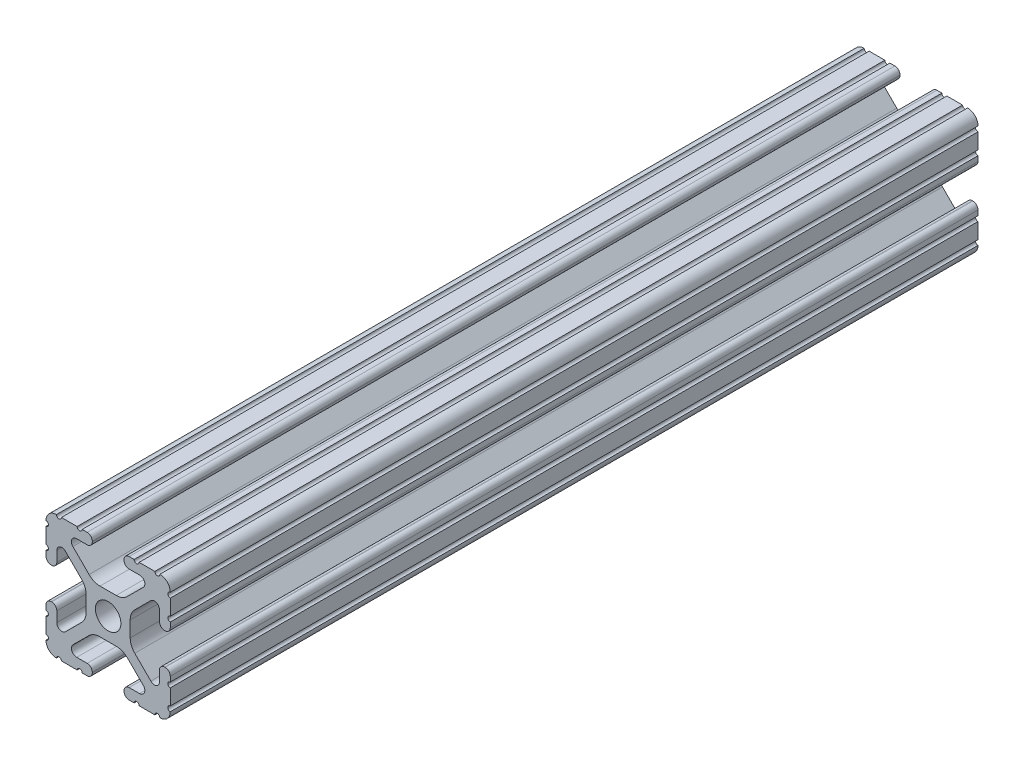
SolidWorks part; units mm, degrees
ref_plane "Front Plane" through (0, 0, 0) normal (0, 0, 1) x (1, 0, 0)
ref_plane "Top Plane" through (0, 0, 0) normal (0, 1, 0) x (1, 0, 0)
ref_plane "Right Plane" through (0, 0, 0) normal (1, 0, 0) x (0, 0, -1)
sketch "Sketch1" plane through (0, 0, 0) normal (0, 0, 1) x (1, 0, 0)
  line L88 (-7.1797, -8.6452) -> (-3.9523, -5.4237)
  line L89 (-1.7093, -4.4958) -> (1.7093, -4.4958)
  line L90 (3.9523, -5.4237) -> (7.1797, -8.6452)
  line L91 (6.4164, -10.4902) -> (4.2875, -10.4902)
  line L92 (3.2385, -11.5392) -> (3.2385, -11.651)
  line L93 (4.2875, -12.7) -> (5.3171, -12.7)
  line L94 (6.3331, -12.7) -> (9.5504, -12.7)
  line L95 (12.7, -9.5504) -> (12.7, -6.3331)
  line L96 (12.7, -5.3171) -> (12.7, -4.2875)
  line L97 (11.651, -3.2385) -> (11.5392, -3.2385)
  line L98 (10.4902, -4.2875) -> (10.4902, -6.4021)
  line L99 (8.7371, -7.1294) -> (5.441, -3.8408)
  line L100 (4.5085, -1.5932) -> (4.5085, 1.5932)
  line L101 (5.441, 3.8408) -> (8.7371, 7.1294)
  line L102 (10.4902, 6.4021) -> (10.4902, 4.2875)
  line L103 (11.5392, 3.2385) -> (11.651, 3.2385)
  line L104 (12.7, 4.2875) -> (12.7, 5.3171)
  line L105 (12.7, 6.3331) -> (12.7, 9.5504)
  line L106 (9.5504, 12.7) -> (6.3331, 12.7)
  line L107 (5.3171, 12.7) -> (4.2875, 12.7)
  line L108 (3.2385, 11.651) -> (3.2385, 11.5392)
  line L109 (4.2875, 10.4902) -> (6.4768, 10.4902)
  line L110 (7.207, 8.7244) -> (3.8983, 5.4232)
  line L111 (1.6558, 4.4958) -> (-1.6558, 4.4958)
  line L112 (-3.8983, 5.4232) -> (-7.207, 8.7244)
  line L113 (-6.4768, 10.4902) -> (-4.2875, 10.4902)
  line L114 (-3.2385, 11.5392) -> (-3.2385, 11.651)
  line L115 (-4.2875, 12.7) -> (-5.3171, 12.7)
  line L116 (-6.3331, 12.7) -> (-9.5504, 12.7)
  line L117 (-12.7, 9.5504) -> (-12.7, 6.3331)
  line L118 (-12.7, 5.3171) -> (-12.7, 4.2875)
  line L119 (-11.651, 3.2385) -> (-11.5392, 3.2385)
  line L120 (-10.4902, 4.2875) -> (-10.4902, 6.4021)
  line L121 (-8.7371, 7.1294) -> (-5.441, 3.8408)
  line L122 (-4.5085, 1.5932) -> (-4.5085, -1.5932)
  line L123 (-5.441, -3.8408) -> (-8.7371, -7.1294)
  line L124 (-10.4902, -6.4021) -> (-10.4902, -4.2875)
  line L125 (-11.5392, -3.2385) -> (-11.651, -3.2385)
  line L126 (-12.7, -4.2875) -> (-12.7, -5.3171)
  line L127 (-12.7, -6.3331) -> (-12.7, -9.5504)
  line L128 (-9.5504, -12.7) -> (-6.3331, -12.7)
  line L129 (-5.3171, -12.7) -> (-4.2875, -12.7)
  line L130 (-3.2385, -11.651) -> (-3.2385, -11.5392)
  line L131 (-4.2875, -10.4902) -> (-6.4164, -10.4902)
  circle A1 centre (0, 0) radius 2.6035
  arc A104 (-7.1797, -8.6452) -> (-6.4164, -10.4902) centre (-6.4164, -9.4098) ccw
  arc A105 (-1.7093, -4.4958) -> (-3.9523, -5.4237) centre (-1.7093, -7.6708) ccw
  arc A106 (3.9523, -5.4237) -> (1.7093, -4.4958) centre (1.7093, -7.6708) ccw
  arc A107 (6.4164, -10.4902) -> (7.1797, -8.6452) centre (6.4164, -9.4098) ccw
  arc A108 (4.2875, -10.4902) -> (3.2385, -11.5392) centre (4.2875, -11.5392) ccw
  arc A109 (3.2385, -11.651) -> (4.2875, -12.7) centre (4.2875, -11.651) ccw
  arc A110 (6.3331, -12.7) -> (5.3171, -12.7) centre (5.8251, -12.7) ccw
  arc A111 (10.5664, -12.6998) -> (9.5504, -12.7) centre (10.0584, -12.7) ccw
  arc A112 (10.5664, -12.6998) -> (12.6998, -10.5664) centre (10.5918, -10.5918) ccw
  arc A113 (12.7, -9.5504) -> (12.6998, -10.5664) centre (12.7, -10.0584) ccw
  arc A114 (12.7, -5.3171) -> (12.7, -6.3331) centre (12.7, -5.8251) ccw
  arc A115 (12.7, -4.2875) -> (11.651, -3.2385) centre (11.651, -4.2875) ccw
  arc A116 (11.5392, -3.2385) -> (10.4902, -4.2875) centre (11.5392, -4.2875) ccw
  arc A117 (8.7371, -7.1294) -> (10.4902, -6.4021) centre (9.4628, -6.4021) ccw
  arc A118 (4.5085, -1.5932) -> (5.441, -3.8408) centre (7.6835, -1.5932) ccw
  arc A119 (5.441, 3.8408) -> (4.5085, 1.5932) centre (7.6835, 1.5932) ccw
  arc A120 (10.4902, 6.4021) -> (8.7371, 7.1294) centre (9.4628, 6.4021) ccw
  arc A121 (10.4902, 4.2875) -> (11.5392, 3.2385) centre (11.5392, 4.2875) ccw
  arc A122 (11.651, 3.2385) -> (12.7, 4.2875) centre (11.651, 4.2875) ccw
  arc A123 (12.7, 6.3331) -> (12.7, 5.3171) centre (12.7, 5.8251) ccw
  arc A124 (12.6998, 10.5664) -> (12.7, 9.5504) centre (12.7, 10.0584) ccw
  arc A125 (12.6998, 10.5664) -> (10.5664, 12.6998) centre (10.5918, 10.5918) ccw
  arc A126 (9.5504, 12.7) -> (10.5664, 12.6998) centre (10.0584, 12.7) ccw
  arc A127 (5.3171, 12.7) -> (6.3331, 12.7) centre (5.8251, 12.7) ccw
  arc A128 (4.2875, 12.7) -> (3.2385, 11.651) centre (4.2875, 11.651) ccw
  arc A129 (3.2385, 11.5392) -> (4.2875, 10.4902) centre (4.2875, 11.5392) ccw
  arc A130 (7.207, 8.7244) -> (6.4768, 10.4902) centre (6.4768, 9.4563) ccw
  arc A131 (1.6558, 4.4958) -> (3.8983, 5.4232) centre (1.6558, 7.6708) ccw
  arc A132 (-3.8983, 5.4232) -> (-1.6558, 4.4958) centre (-1.6558, 7.6708) ccw
  arc A133 (-6.4768, 10.4902) -> (-7.207, 8.7244) centre (-6.4768, 9.4563) ccw
  arc A134 (-4.2875, 10.4902) -> (-3.2385, 11.5392) centre (-4.2875, 11.5392) ccw
  arc A135 (-3.2385, 11.651) -> (-4.2875, 12.7) centre (-4.2875, 11.651) ccw
  arc A136 (-6.3331, 12.7) -> (-5.3171, 12.7) centre (-5.8251, 12.7) ccw
  arc A137 (-10.5664, 12.6998) -> (-9.5504, 12.7) centre (-10.0584, 12.7) ccw
  arc A138 (-10.5664, 12.6998) -> (-12.6998, 10.5664) centre (-10.5918, 10.5918) ccw
  arc A139 (-12.7, 9.5504) -> (-12.6998, 10.5664) centre (-12.7, 10.0584) ccw
  arc A140 (-12.7, 5.3171) -> (-12.7, 6.3331) centre (-12.7, 5.8251) ccw
  arc A141 (-12.7, 4.2875) -> (-11.651, 3.2385) centre (-11.651, 4.2875) ccw
  arc A142 (-11.5392, 3.2385) -> (-10.4902, 4.2875) centre (-11.5392, 4.2875) ccw
  arc A143 (-8.7371, 7.1294) -> (-10.4902, 6.4021) centre (-9.4628, 6.4021) ccw
  arc A144 (-4.5085, 1.5932) -> (-5.441, 3.8408) centre (-7.6835, 1.5932) ccw
  arc A145 (-5.441, -3.8408) -> (-4.5085, -1.5932) centre (-7.6835, -1.5932) ccw
  arc A146 (-10.4902, -6.4021) -> (-8.7371, -7.1294) centre (-9.4628, -6.4021) ccw
  arc A147 (-10.4902, -4.2875) -> (-11.5392, -3.2385) centre (-11.5392, -4.2875) ccw
  arc A148 (-11.651, -3.2385) -> (-12.7, -4.2875) centre (-11.651, -4.2875) ccw
  arc A149 (-12.7, -6.3331) -> (-12.7, -5.3171) centre (-12.7, -5.8251) ccw
  arc A150 (-12.6998, -10.5664) -> (-12.7, -9.5504) centre (-12.7, -10.0584) ccw
  arc A151 (-12.6998, -10.5664) -> (-10.5664, -12.6998) centre (-10.5918, -10.5918) ccw
  arc A152 (-9.5504, -12.7) -> (-10.5664, -12.6998) centre (-10.0584, -12.7) ccw
  arc A153 (-5.3171, -12.7) -> (-6.3331, -12.7) centre (-5.8251, -12.7) ccw
  arc A154 (-4.2875, -12.7) -> (-3.2385, -11.651) centre (-4.2875, -11.651) ccw
  arc A155 (-3.2385, -11.5392) -> (-4.2875, -10.4902) centre (-4.2875, -11.5392) ccw
extrude "Boss-Extrude1" add sketch "Sketch1" along normal mid plane 304.8
sketch "Sketch3" plane through (0, 0, 152.4) normal (0, 0, 1) x (1, 0, 0)
  line L1 (-12.7, 12.7) -> (12.7, 12.7)
  line L2 (-12.7, 12.7) -> (-12.7, -12.7)
  line L3 (-12.7, -12.7) -> (12.7, -12.7)
  line L4 (12.7, 12.7) -> (12.7, -12.7)
  dimension "D1" = 12.7
  dimension "D2" = 25.4
  dimension "D3" = 25.4
  dimension "D4" = 12.7
extrude "Cut-Extrude1" cut sketch "Sketch3" against normal blind 139.7
